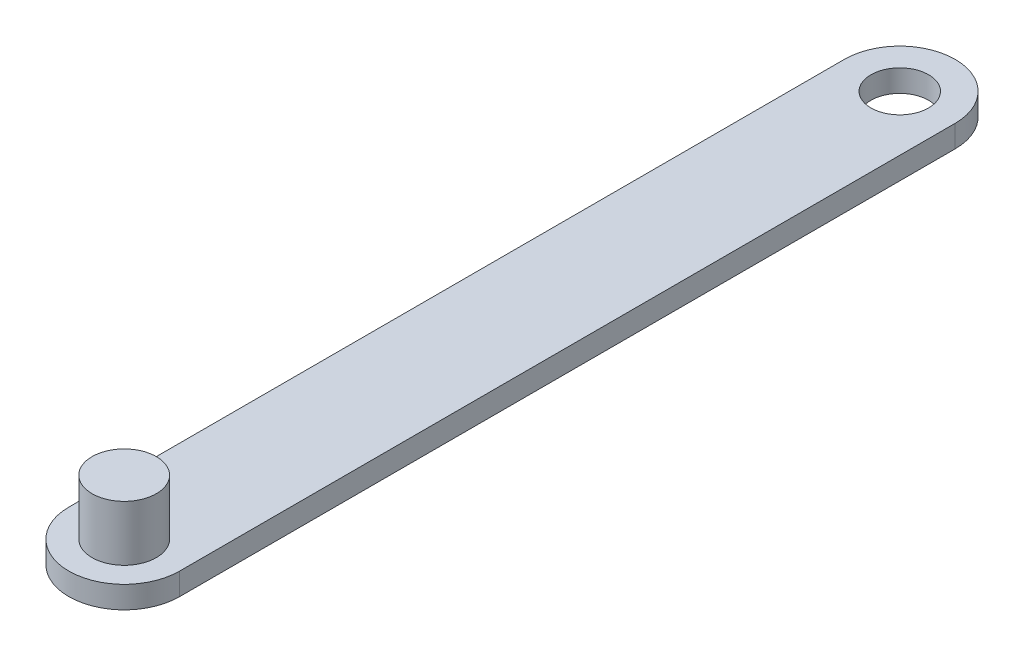
SolidWorks part; units mm, degrees
ref_plane "Front Plane" through (0, 0, 0) normal (0, 0, 1) x (1, 0, 0)
ref_plane "Top Plane" through (0, 0, 0) normal (0, 1, 0) x (1, 0, 0)
ref_plane "Right Plane" through (0, 0, 0) normal (1, 0, 0) x (0, 0, -1)
sketch "Sketch1" plane through (0, 0, 0) normal (0, 1, 0) x (1, 0, 0)
  line L2 (0, 0) -> (0, 70)
  line L4 (10, 0) -> (10, 70.005)
  arc A0 (10, 70.005) -> (0, 70) centre (5, 70.0025) ccw
  arc A1 (0, 0) -> (10, 0) centre (5, 0) ccw
  dimension "D1" = 70
  dimension "D2" = 10
extrude "Boss-Extrude1" add sketch "Sketch1" along normal blind 2
sketch "Sketch2" plane through (0, 2, 0) normal (0, 1, 0) x (1, 0, 0)
  circle A0 centre (5, 70) radius 2.6
extrude "Cut-Extrude1" cut sketch "Sketch2" against normal blind 2
sketch "Sketch3" plane through (0, 2, 0) normal (0, 1, 0) x (1, 0, 0)
  circle A0 centre (5, 0) radius 2.9
extrude "Boss-Extrude2" add sketch "Sketch3" along normal blind 5
